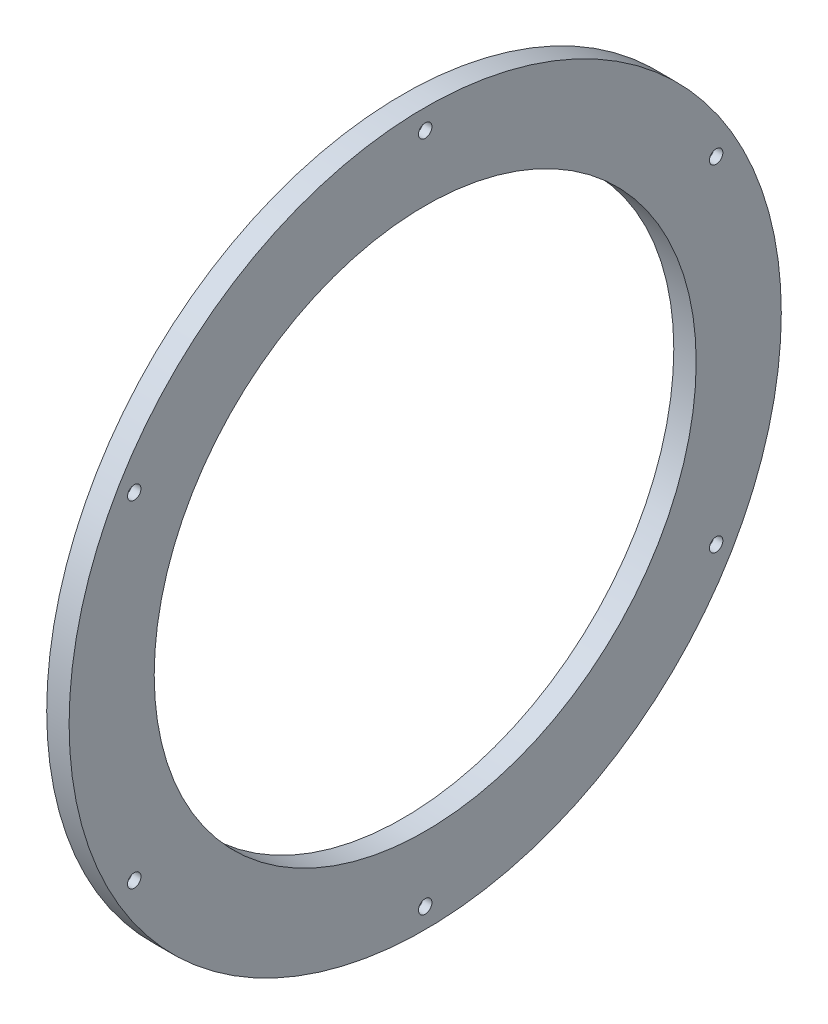
SolidWorks part; units mm, degrees
material "Ductile Iron"
ref_plane "Front Plane" through (0, 0, 0) normal (0, 0, 1) x (1, 0, 0)
ref_plane "Top Plane" through (0, 0, 0) normal (0, 1, 0) x (1, 0, 0)
ref_plane "Right Plane" through (0, 0, 0) normal (1, 0, 0) x (0, 0, -1)
sketch "Sketch1" plane through (0, 0, 0) normal (1, 0, 0) x (0, 0, -1)
  circle A0 centre (0, 0) radius 121
  circle A1 centre (0, 0) radius 159
  dimension "D1" = 242
  dimension "D2" = 318
extrude "Boss-Extrude1" add sketch "Sketch1" along normal blind 10
hole_wizard "CBORE for M5 Hex Head Bolt2" positions "Sketch13" profile "Sketch14" counterbore size "M5" standard "ISO"
sketch "Sketch13" plane through (0, 0, 0) normal (-1, 0, 0) x (0, 0, 1)
  line L0 (0, -1000) -> (0, 49000) construction
  circle A0 centre (0, 0) radius 150 construction
  point P0 (0, 150)
  point P20 (129.9038, 75)
  point P21 (129.9038, -75)
  point P22 (0, -150)
  point P23 (-129.9038, -75)
  point P24 (-129.9038, 75)
  point P25 (0, 0)
  dimension "D1" = 300
  dimension "D2" = 6
sketch "Sketch14" plane through (0, 150, 0) normal (0, 1, 0) x (0, 0, 1)
  line L0 (0, 0) -> (0, 14.8026)
  line L1 (0, 14.8026) -> (3, 13)
  line L2 (3, 13) -> (3, 6)
  line L3 (3, 6) -> (6, 6)
  line L4 (6, 6) -> (6, 0)
  line L5 (6, 0) -> (0, 0)
  line L10 (0, 14.8026) -> (-3, 13) construction
  line L11 (0, -6.35) -> (0, 107.95) construction
  dimension "Hole Dia." = 6
  dimension "Hole Depth" = 13
  dimension "C'Bore Dia." = 12
  dimension "C'Bore Depth" = 6
  dimension "Drill Angle" = 118
